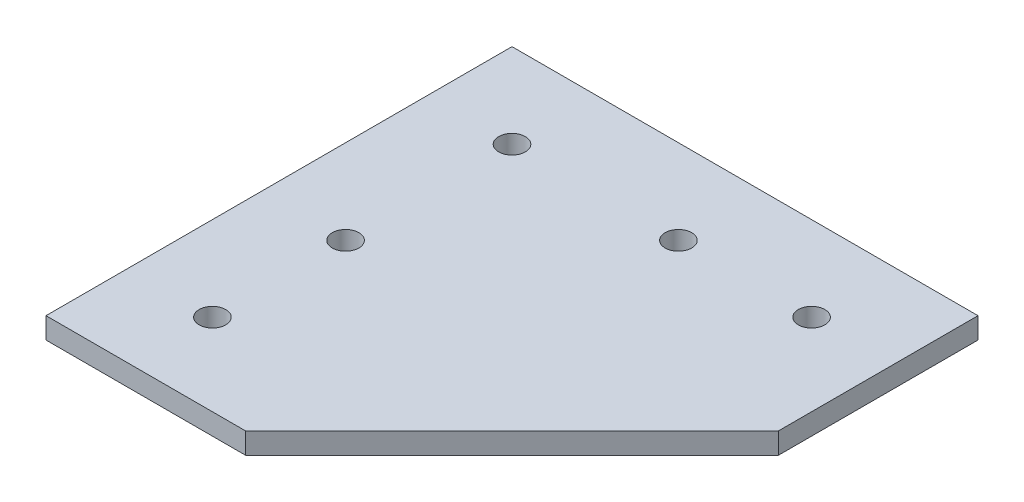
SolidWorks part; units mm, degrees
ref_plane "Front Plane" through (0, 0, 0) normal (0, 0, 1) x (1, 0, 0)
ref_plane "Top Plane" through (0, 0, 0) normal (0, 1, 0) x (1, 0, 0)
ref_plane "Right Plane" through (0, 0, 0) normal (1, 0, 0) x (0, 0, -1)
sketch "Sketch2" plane through (0, 0, 0) normal (0, 1, 0) x (1, 0, 0)
  line L1 (35, -35) -> (-35, -35)
  line L2 (35, -35) -> (35, 35)
  line L3 (35, 35) -> (-35, 35)
  line L4 (-35, -35) -> (-35, 35)
  line L5 (35, -35) -> (-35, 35) construction
  line L6 (35, 35) -> (-35, -35) construction
  point P0 (0, 0)
  dimension "D1" = 70
  dimension "D2" = 70
extrude "Boss-Extrude1" add sketch "Sketch2" along normal blind 3.175
sketch "Sketch6" plane through (0, 3.175, 0) normal (0, 1, 0) x (1, 0, 0)
  line L1 (35, 35) -> (-35, 35) construction
  line L3 (-35, 35) -> (-35, -35) construction
  point P0 (-22.3, 22.3)
  point P2 (22.7, 22.3)
  point P4 (2.7, 22.3)
  point P6 (-22.3, -2.7)
  point P8 (-22.3, -22.7)
  point P13 (0, 0)
  point P14 (0, 0)
  dimension "D1" = 25
  dimension "D2" = 20
  dimension "D3" = 12.7
  dimension "D4" = 12.7
  dimension "D5" = 25
  dimension "D6" = 20
hole_wizard "Ø4.0mm Dowel Hole1" positions "Sketch6" profile "Sketch7" hole size "Ø4.0" standard "ANSI Metric" end condition through all
sketch "Sketch7" plane through (-22.3, 3.175, -22.3) normal (1, 0, 0) x (0, 0, 1)
  line L0 (0, 0) -> (0, 3.175)
  line L1 (0, 3.175) -> (2, 3.175)
  line L2 (2, 3.175) -> (2, 0)
  line L5 (2, 0) -> (0, 0)
  line L11 (0, -6.35) -> (0, 107.95) construction
  dimension "Thru Hole Dia." = 4
  dimension "Thru Hole Depth" = 3.175
sketch "Sketch8" plane through (0, 3.175, 0) normal (0, 1, 0) x (1, 0, 0)
  line L0 (-5, -35) -> (35, 5)
  line L1 (-35, -35) -> (35, -35) construction
  line L2 (35, -35) -> (35, 35) construction
  line L3 (35, 5) -> (35, -35)
  line L4 (35, -35) -> (-5, -35)
  dimension "D1" = 45
  dimension "D2" = 40
extrude "Cut-Extrude1" cut sketch "Sketch8" against normal through all
